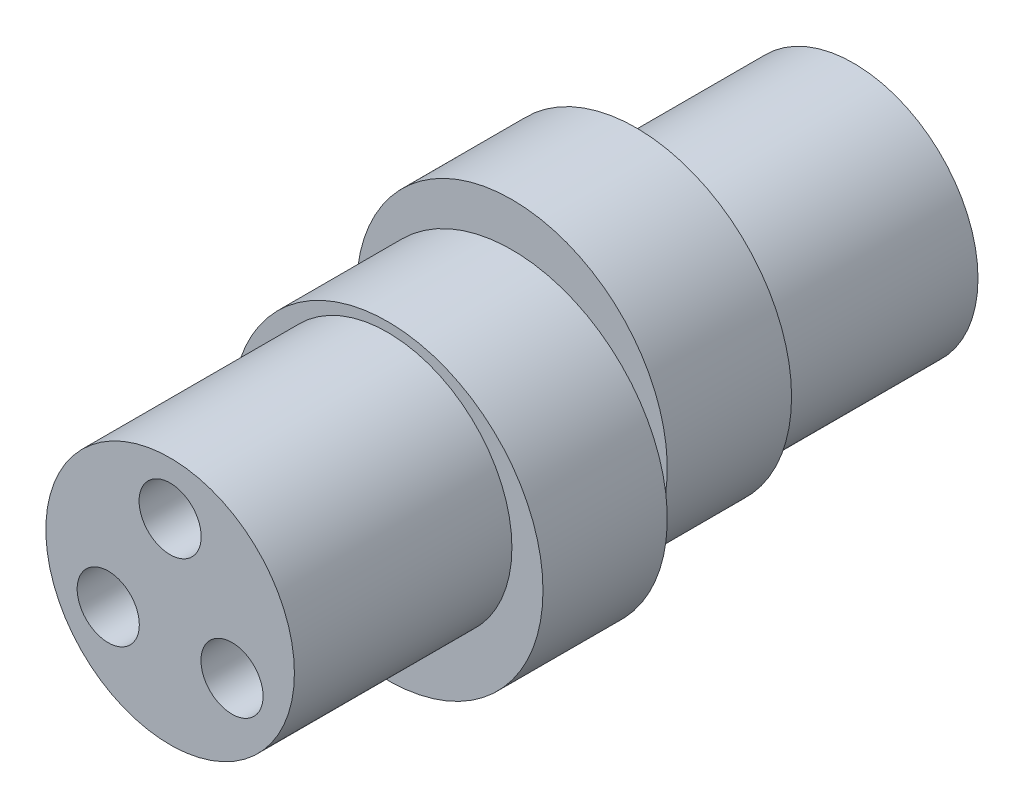
SolidWorks part; units mm, degrees
material "6061 Alloy"
ref_plane "Front Plane" through (0, 0, 0) normal (0, 0, 1) x (1, 0, 0)
ref_plane "Top Plane" through (0, 0, 0) normal (0, 1, 0) x (1, 0, 0)
ref_plane "Right Plane" through (0, 0, 0) normal (1, 0, 0) x (0, 0, -1)
sketch "Sketch1" plane through (0, 0, 0) normal (0, 0, 1) x (1, 0, 0)
  circle A2 centre (0, 0.7) radius 5
  dimension "D1" = 10
  dimension "D2" = 0.7
extrude "Boss-Extrude1" add sketch "Sketch1" along normal blind 4 contours A2
sketch "Sketch2" plane through (0, 0, 0) normal (0, 0, 1) x (1, 0, 0)
  circle A0 centre (0, -0.7) radius 5
  dimension "D1" = 10
  dimension "D2" = 0.7
extrude "Boss-Extrude2" add sketch "Sketch2" along normal blind 4 from surface at 4 starting at face at (5, 0.7, 4)
sketch "Sketch5" plane through (0, 0, 0) normal (0, 0, 1) x (1, 0, 0)
  circle A1 centre (0, 0) radius 4
  point P13 (0, 0)
  dimension "D2" = 8
extrude "Boss-Extrude5" add sketch "Sketch5" against normal blind 7 and the other way blind 15
sketch "Sketch7" plane through (0, 0, 0) normal (0, 0, 1) x (1, 0, 0)
  circle A0 centre (0, -0.7) radius 5
  circle A1 centre (0, -0.7) radius 6
  dimension "D1" = 10
  dimension "D2" = 0.7
  dimension "D3" = 12
sketch "Sketch8" plane through (0, 0, 0) normal (0, 0, 1) x (1, 0, 0)
  circle A0 centre (0, 0.7) radius 5
  circle A1 centre (0, 0.7) radius 6
  dimension "D1" = 12
  dimension "D2" = 10
  dimension "D3" = 0.7
sketch "Sketch9" plane through (0, 0, 0) normal (0, 0, 1) x (1, 0, 0)
  line L0 (0, 0) -> (0, 3.5226) construction
  circle A1 centre (0, 2.3) radius 1
  circle A2 centre (1.9919, -1.15) radius 1
  circle A3 centre (-1.9919, -1.15) radius 1
  point P12 (0, 0)
  dimension "D1" = 2
  dimension "D2" = 2.3
  dimension "D3" = 3
extrude "Cut-Extrude1" cut sketch "Sketch9" against normal through all and the other way through all contours A1 L0 | L0 A1 | A3 | A2
sketch "Sketch10" plane through (0, 0, 0) normal (0, 0, 1) x (1, 0, 0)
  circle A0 centre (0, 0) radius 6
  dimension "D1" = 12
equation "\"d1\"= 0.7"
equation "\"d2\"=10"
equation "\"d3\"=7"
equation "\"D1@Sketch1\"= \"d2\""
equation "\"D2@Sketch1\"=\"d1\""
equation "\"D1@Sketch2\" = \"d2\""
equation "\"D2@Sketch2\" = \"d1\""
equation "\"d4\"=4"
equation "\"D2@Sketch7\"=\"d1\""
equation "\"D1@Sketch7\"=\"d2\""
equation "\"D3@Sketch7\"=\"d2\"+2"
equation "\"D1@Sketch8\"=\"d2\"+2"
equation "\"D2@Sketch8\"=\"d2\""
equation "\"D3@Sketch8\"=\"d1\""
equation "\"D1@Boss-Extrude2\"=\"d4\""
equation "\"D1@Boss-Extrude1\"=\"d4\""
